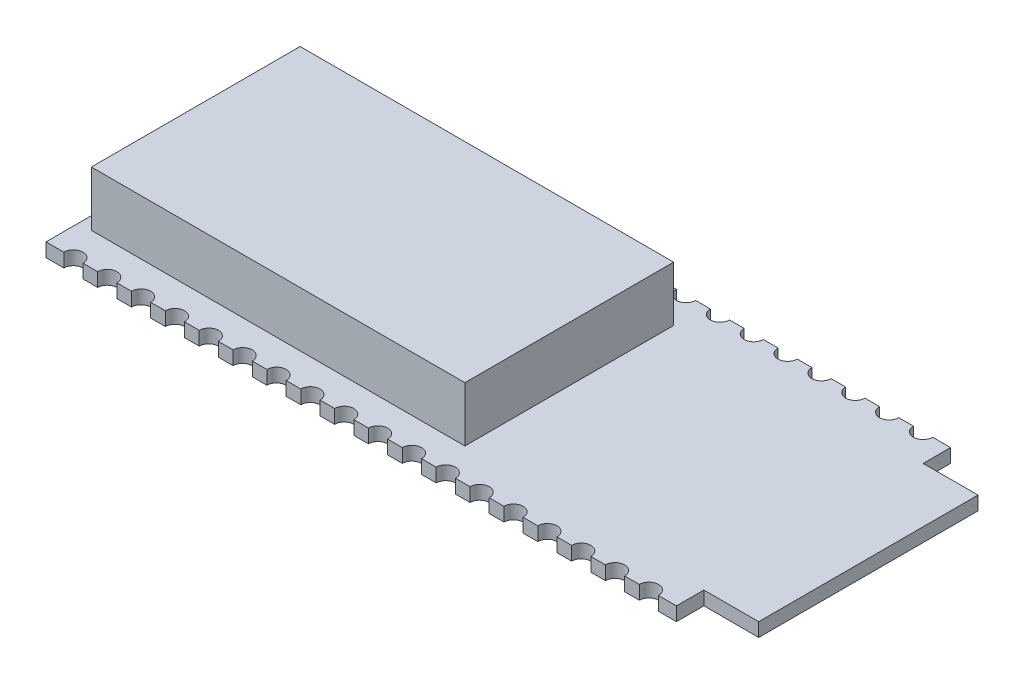
SolidWorks part; units mm, degrees
ref_plane "Front Plane" through (0, 0, 0) normal (0, 0, 1) x (1, 0, 0)
ref_plane "Top Plane" through (0, 0, 0) normal (0, 1, 0) x (1, 0, 0)
ref_plane "Right Plane" through (0, 0, 0) normal (1, 0, 0) x (0, 0, -1)
sketch "Sketch4" plane through (0, 0, 0) normal (0, 1, 0) x (1, 0, 0)
  line L1 (-23, -10) -> (23, -10)
  line L2 (-23, -10) -> (-23, 10)
  line L3 (-23, 10) -> (23, 10)
  line L4 (23, -10) -> (23, -8)
  line L5 (-23, -10) -> (23, 10) construction
  line L6 (-23, 10) -> (23, -10) construction
  line L7 (23, 8) -> (23, 10)
  line L8 (23, 8) -> (27, 8)
  line L10 (23, -8) -> (27, -8)
  line L11 (27, 8) -> (27, -8)
  point P0 (0, 0)
  point P9 (23, 0)
extrude "Boss-Extrude2" add sketch "Sketch4" along normal blind 1
sketch "Sketch5" plane through (0, 1, 0) normal (0, 1, 0) x (1, 0, 0)
  line L0 (-23, 10) -> (-21, 10) construction
  line L1 (23, 10) -> (-23, 10) construction
  circle A0 centre (-21, 10) radius 0.7
extrude "Cut-Extrude2" cut sketch "Sketch5" against normal blind 1
pattern_linear "LPattern2" count 18 spacing 2.47 along (1, 0, 0) of "Cut-Extrude2"
mirror "Mirror1" about plane through (0, 0, 0) normal (0, 0, 1) of "LPattern2", "Cut-Extrude2"
sketch "Sketch6" plane through (0, 1, 0) normal (0, 1, 0) x (1, 0, 0)
  line L0 (5.1797, 7.6161) -> (5.1797, -7.6161)
  line L1 (5.1797, -7.6161) -> (-22.0747, -7.6161)
  line L3 (5.1797, 7.6161) -> (-22.0747, 7.6161)
  line L4 (-22.0747, -7.6161) -> (-22.0747, 7.6161)
  line L5 (5.1797, -1.7871) -> (-22.0747, 7.6161) construction
  line L6 (5.1797, 1.7871) -> (-22.0747, -7.6161) construction
  point P0 (0, 0)
extrude "Boss-Extrude3" add sketch "Sketch6" along normal blind 4
sketch "Sketch7" plane through (0, 0, 0) normal (0, 1, 0) x (1, 0, 0)
  line L0 (332.8152, 640.0485) -> (1513.4819, 640.0485) construction
